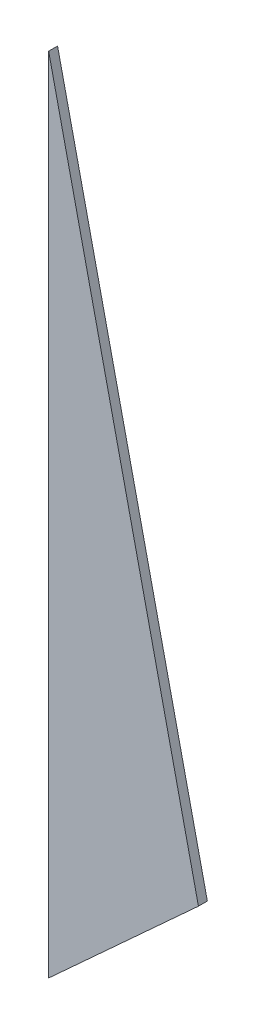
SolidWorks part; units mm, degrees
ref_plane "Front Plane" through (0, 0, 0) normal (0, 0, 1) x (1, 0, 0)
ref_plane "Top Plane" through (0, 0, 0) normal (0, 1, 0) x (1, 0, 0)
ref_plane "Right Plane" through (0, 0, 0) normal (1, 0, 0) x (0, 0, -1)
sketch "Sketch1" plane through (0, 0, 0) normal (0, 0, 1) x (1, 0, 0)
  line L0 (0, -45) -> (0, 45)
  line L1 (0, 45) -> (16.7943, -29.6323)
  line L2 (0, -45) -> (16.7943, -29.6323)
  line L4 (18, 252.3816) -> (18, -45) construction
  point P4 (0, 0)
  point P7 (16.7943, -29.6323)
extrude "Boss-Extrude1" add sketch "Sketch1" along normal mid plane 1
